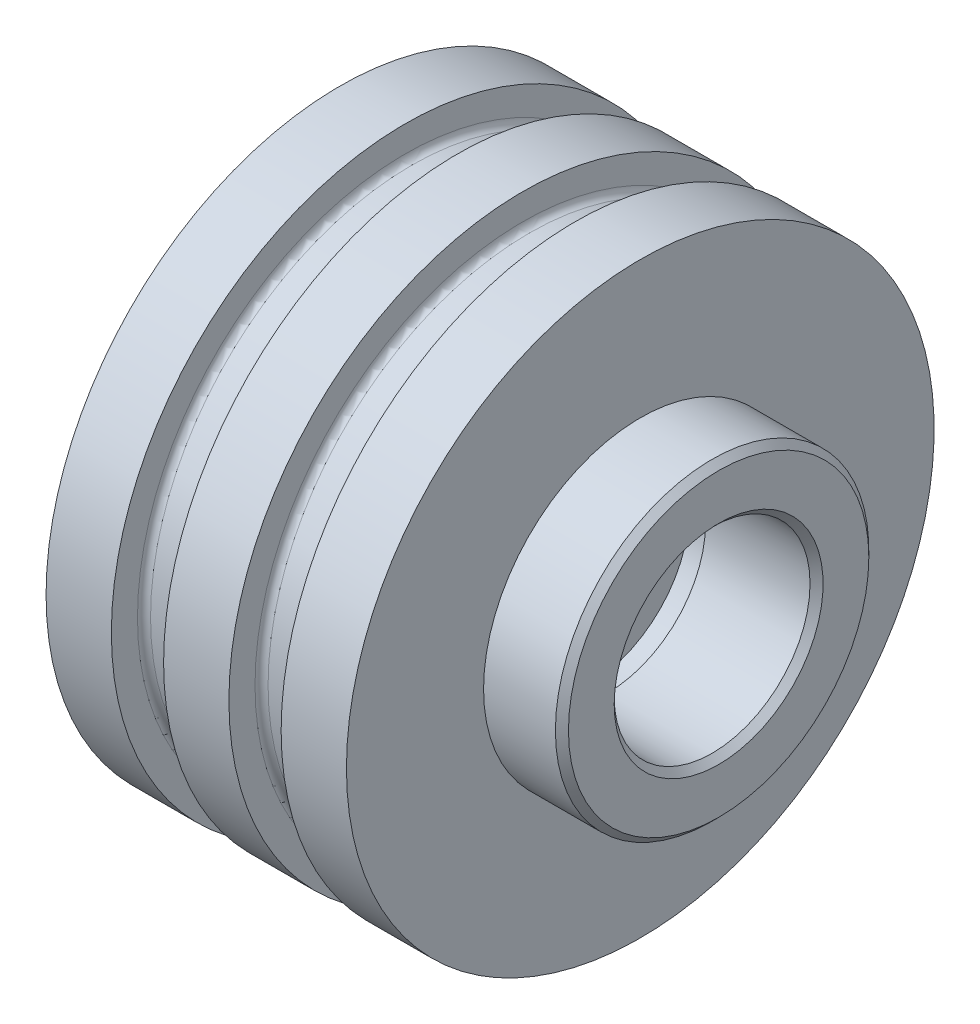
SolidWorks part; units mm, degrees
material "Алюминиевая бронза"
ref_plane "Спереди" through (0, 0, 0) normal (0, 0, 1) x (1, 0, 0)
ref_plane "Сверху" through (0, 0, 0) normal (0, 1, 0) x (1, 0, 0)
ref_plane "Справа" through (0, 0, 0) normal (1, 0, 0) x (0, 0, -1)
sketch "Эскиз1" plane through (0, 0, 0) normal (0, 0, 1) x (1, 0, 0)
  line L0 (2, 0) -> (65.1949, 0) construction
  line L1 (0, 42) -> (0, 45)
  line L2 (0, 45) -> (10, 45)
  line L3 (46, 45) -> (46, 24)
  line L4 (46, 24) -> (57, 24)
  line L5 (58, 23) -> (58, 0)
  line L10 (58, 0) -> (2, 0)
  line L12 (57, 24) -> (58, 23)
  line L13 (10, 45) -> (10, 41)
  line L14 (11, 40) -> (17, 40)
  line L15 (18, 41) -> (18, 45)
  line L16 (0, 42) -> (2, 42)
  line L17 (2, 42) -> (2, 0)
  line L18 (18, 45) -> (28, 45)
  line L19 (28, 45) -> (28, 41)
  line L20 (29, 40) -> (35, 40)
  line L21 (36, 41) -> (36, 45)
  line L22 (36, 45) -> (46, 45)
  arc A0 (17, 40) -> (18, 41) centre (17, 41) ccw
  arc A1 (10, 41) -> (11, 40) centre (11, 41) ccw
  arc A2 (28, 41) -> (29, 40) centre (29, 41) ccw
  arc A3 (35, 40) -> (36, 41) centre (35, 41) ccw
  point P0 (0, 43.5)
  point P7 (58, 24)
  point P26 (18, 40)
  point P29 (10, 40)
  point P35 (28, 40)
  point P38 (36, 40)
  dimension "D18" = 1
  dimension "D21" = 1
  dimension "D1" = 90
  dimension "D2" = 48
  dimension "D7" = 58
  dimension "D8" = 12
  dimension "D11" = 1
  dimension "D12" = 45
  dimension "D13" = 84
  dimension "D14" = 2
  dimension "D15" = 8
  dimension "D16" = 5
  dimension "D17" = 10
  dimension "D19" = 10
  dimension "D20" = 8
revolve "Повернуть1" add sketch "Эскиз1" angle 360 about L0
sketch "Эскиз2" plane through (0, 0, 0) normal (0, 0, 1) x (1, 0, 0)
  line L0 (0, 0) -> (78.0067, 0) construction
  line L1 (58, 0) -> (58, 15)
  line L2 (58, 15) -> (41, 15)
  line L3 (41, 15) -> (41, 15.5)
  line L4 (41, 15.5) -> (38, 15.5)
  line L5 (38, 15.5) -> (38, 0)
  line L6 (38, 0) -> (58, 0)
  line L7 (58, -23) -> (58, 23) construction
  dimension "D1" = 3
  dimension "D2" = 20
  dimension "D3" = 30
  dimension "D4" = 31
revolve "Вырез-Повернуть1" cut sketch "Эскиз2" angle 360 about L0
chamfer "Фаска1" distance 1 angle 45 1 edges at (58, 0, 15)
